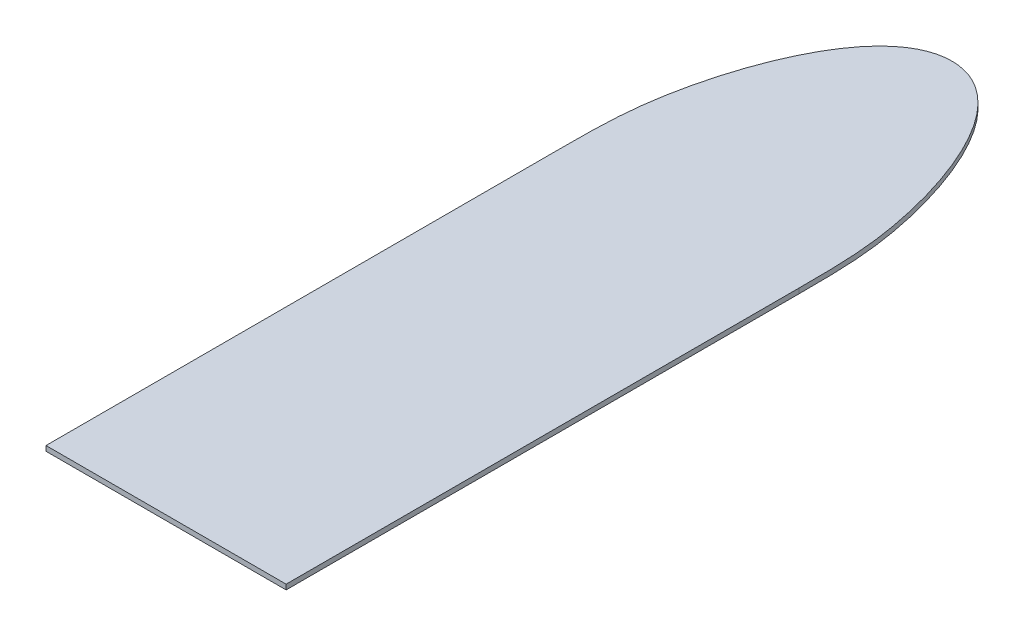
SolidWorks part; units mm, degrees
ref_plane "Front" through (0, 0, 0) normal (0, 0, 1) x (1, 0, 0)
ref_plane "Top" through (0, 0, 0) normal (0, 1, 0) x (1, 0, 0)
ref_plane "Right" through (0, 0, 0) normal (1, 0, 0) x (0, 0, -1)
sketch "Sketch2" plane through (0, 0, 0) normal (0, 1, 0) x (1, 0, 0)
  line L0 (139.7, -1270) -> (139.7, 63.5)
  line L8 (0, -1460.5) -> (441.3665, -1460.5) construction
  line L9 (0, 381) -> (319.7263, 381) construction
  spline S0 degree 3 poles (0, -1460.5) (108.685, -1460.5) (137.2012, -1361.3853) (139.7, -1312.0378) (139.7, -1270) knots 0 0 0 0 0.140311 0.20061 0.20061 0.20061 0.20061
  spline S2 degree 3 poles (139.7, 63.5) (139.7, 105.4099) (138.7759, 206.4957) (73.5078, 381) (0, 381) knots 0.803818 0.803818 0.803818 0.803818 0.866735 1 1 1 1
  point P36 (70.6307, -1446.9472)
sketch "Sketch3" plane through (0, 0, 0) normal (0, 1, 0) x (1, 0, 0)
  line L0 (0, 381) -> (0, -1460.5)
  line L1 (139.7, -1270) -> (139.7, 63.5) construction
  line L2 (139.7, -1270) -> (139.7, 63.5)
  spline S0 degree 3 poles (1025.6675, -3831.9969) (-39.0223, -26.9755) (418.1083, -122.1769) (-293.9095, 1116.6594) (-981.356, -3470.7577) knots 0.474027 0.474027 0.474027 0.474027 0.866735 1.310287 1.310287 1.310287 1.310287 only from (139.7, 63.5) to (0, 381) construction
  spline S1 degree 3 poles (-3210.7154, 892.7422) (-54.9132, -1919.6755) (220.175, -1221.285) (106.9015, -1265.7705) (210.1254, 2729.0414) knots -0.329125 -0.329125 -0.329125 -0.329125 0.140311 0.445941 0.445941 0.445941 0.445941 only from (0, -1460.5) to (139.7, -1270) construction
  spline S2 degree 3 poles (139.7, 63.5) (139.7, 105.4099) (138.7759, 206.4957) (73.5078, 381) (0, 381) knots 0.803818 0.803818 0.803818 0.803818 0.866735 1 1 1 1
  spline S3 degree 3 poles (0, -1460.5) (108.685, -1460.5) (137.2012, -1361.3853) (139.7, -1312.0378) (139.7, -1270) knots 0 0 0 0 0.140311 0.20061 0.20061 0.20061 0.20061
extrude "Boss-Extrude1" add sketch "Sketch3" along normal blind 5.842
sketch "Sketch4" plane through (0, 0, 0) normal (0, 1, 0) x (1, 0, 0)
  line L0 (139.7, -1270) -> (139.7, 63.5) construction
  line L1 (0, -533.4) -> (0, -1460.5)
  line L2 (139.7, -533.4) -> (139.7, -1460.5)
  line L3 (0, -533.4) -> (139.7, -533.4)
  line L4 (0, -1460.5) -> (441.3665, -1460.5) construction
  line L5 (139.7, -1460.5) -> (0, -1460.5)
  dimension "D1" = 914.4
extrude "Cut-Extrude1" cut sketch "Sketch4" along normal through all
mirror "Mirror1" about plane through (0, 0, 0) normal (1, 0, 0) of bodies 103 101
